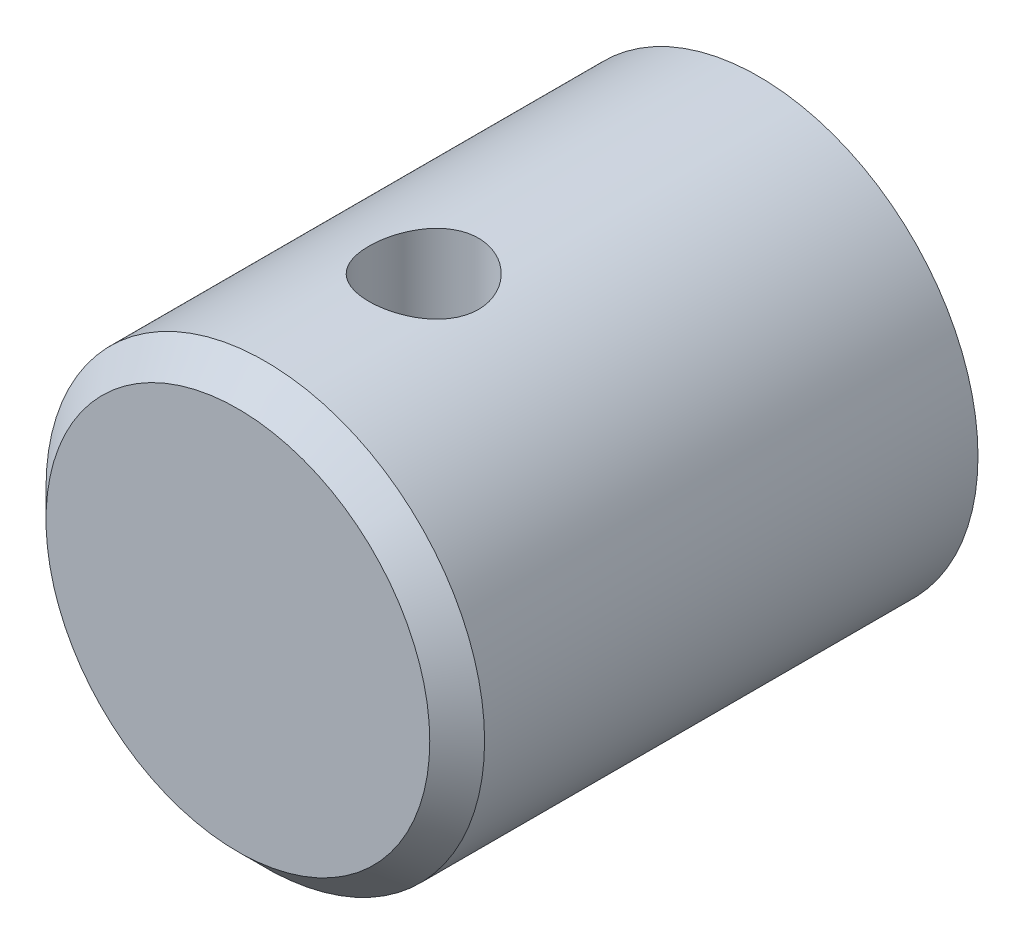
SolidWorks part; units mm, degrees
ref_plane "Front Plane" through (0, 0, 0) normal (0, 0, 1) x (1, 0, 0)
ref_plane "Top Plane" through (0, 0, 0) normal (0, 1, 0) x (1, 0, 0)
ref_plane "Right Plane" through (0, 0, 0) normal (1, 0, 0) x (0, 0, -1)
sketch "Sketch1" plane through (0, 0, 0) normal (0, 0, 1) x (1, 0, 0)
  circle A0 centre (0, 0) radius 8
  dimension "D1" = 16
extrude "Boss-Extrude1" add sketch "Sketch1" along normal blind 19
sketch "Sketch2" plane through (0, 0, 0) normal (0, 1, 0) x (1, 0, 0)
  circle A0 centre (0, -12.2213) radius 2
  point P2 (0, -10.3557)
  point P4 (0, -11)
  point P5 (0, -11.8609)
  point P6 (0, -12.2213)
  dimension "D1" = 4
extrude "Cut-Extrude1" cut sketch "Sketch2" against normal mid plane 48
chamfer "Chamfer1" distance 1 angle 45 1 edges at (8, 0, 19)
